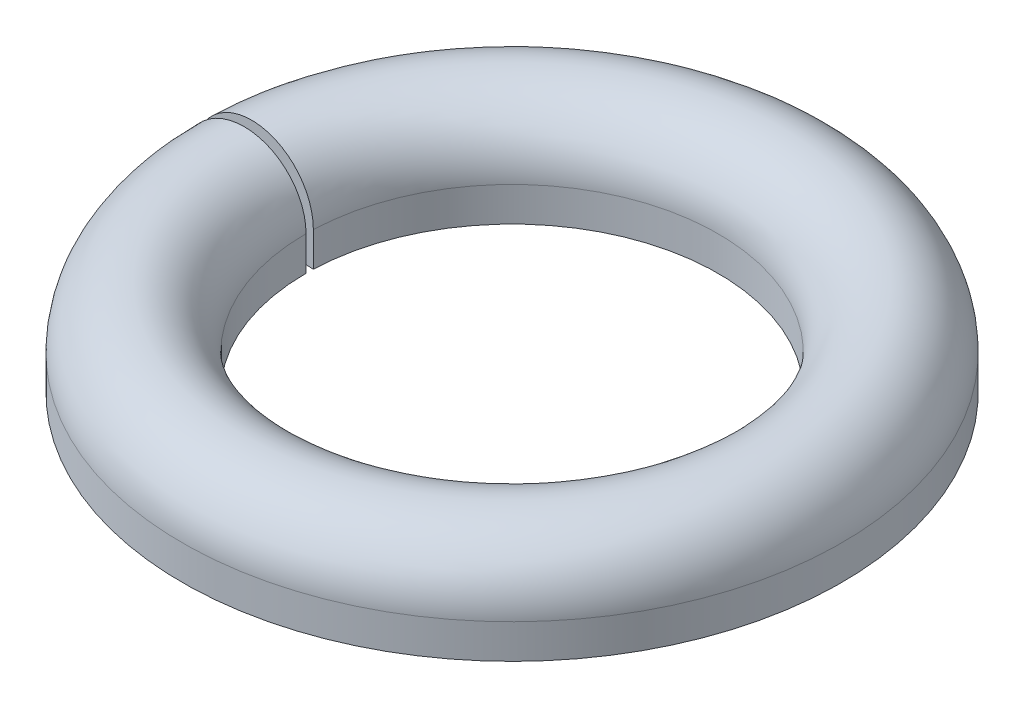
SolidWorks part; units mm, degrees
ref_plane "Front Plane" through (0, 0, 0) normal (0, 0, 1) x (1, 0, 0)
ref_plane "Top Plane" through (0, 0, 0) normal (0, 1, 0) x (1, 0, 0)
ref_plane "Right Plane" through (0, 0, 0) normal (1, 0, 0) x (0, 0, -1)
sketch "Sketch1" plane through (0, 0, 0) normal (0, 0, 1) x (1, 0, 0)
  line L0 (-15, 0) -> (-24, 0)
  line L6 (0, 0) -> (0, 18.4525) construction
  line L7 (-24, 0) -> (-24, 2.5)
  line L8 (-15, 0) -> (-15, 2.5)
  line L9 (-16.5, 1.5) -> (-16.5, 2.5)
  line L10 (-16.5, 1.5) -> (-22.5, 1.5)
  line L11 (-22.5, 1.5) -> (-22.5, 2.5)
  arc A3 (-24, 2.5) -> (-15, 2.5) centre (-19.5, 2.5) cw
  arc A4 (-22.5, 2.5) -> (-16.5, 2.5) centre (-19.5, 2.5) cw
  point P6 (-19.5, 7)
  dimension "D1" = 48
  dimension "D2" = 9
  dimension "D3" = 7
  dimension "D4" = 1.5
revolve "Revolve1" add sketch "Sketch1" angle 358 about L6
